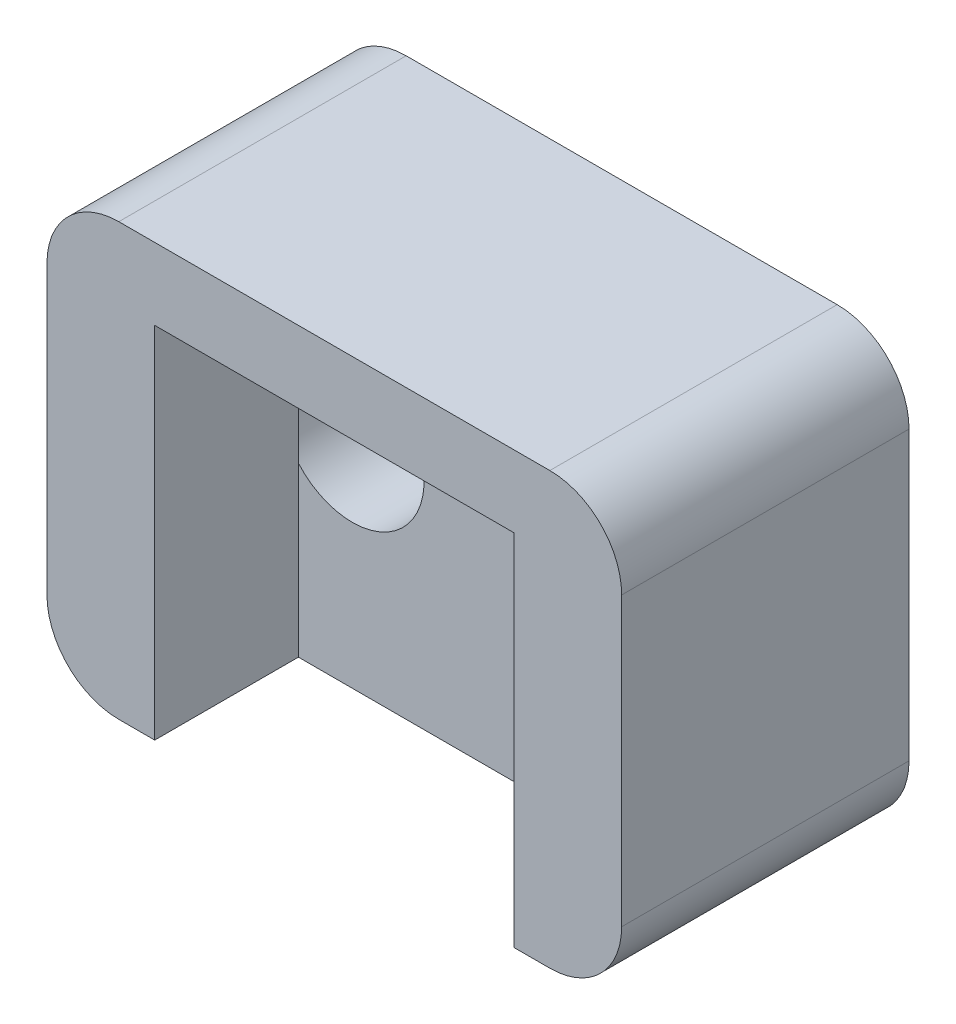
SolidWorks part; units mm, degrees
ref_plane "Front Plane" through (0, 0, 0) normal (0, 0, 1) x (1, 0, 0)
ref_plane "Top Plane" through (0, 0, 0) normal (0, 1, 0) x (1, 0, 0)
ref_plane "Right Plane" through (0, 0, 0) normal (1, 0, 0) x (0, 0, -1)
sketch "Sketch1" plane through (0, 0, 0) normal (0, 0, 1) x (1, 0, 0)
  line L0 (-20, 0) -> (20, 0) construction
  line L1 (-20, 15) -> (20, 15)
  line L2 (-20, 15) -> (-20, -15)
  line L3 (-20, -15) -> (20, -15)
  line L4 (20, 15) -> (20, -15)
  line L5 (-20, 15) -> (20, -15) construction
  line L6 (-20, -15) -> (20, 15) construction
  line L7 (-20, 15) -> (0, -15) construction
  line L8 (0, -15) -> (20, 15) construction
  point P0 (0, 0)
  dimension "D1" = 40
  dimension "D2" = 30
extrude "Boss-Extrude1" add sketch "Sketch1" along normal blind 20
fillet "Fillet1" radius 5 4 edges at (20, 15, 10) (20, -15, 10) (-20, -15, 10) (-20, 15, 10)
sketch "Sketch2" plane through (0, 0, 0) normal (0, 0, -1) x (-1, 0, 0)
  line L0 (-17.5, 7.5) -> (0, -7.5) construction
  line L1 (-17.5, 7.5) -> (17.5, 7.5)
  line L2 (-17.5, 7.5) -> (-17.5, -7.5)
  line L3 (-17.5, -7.5) -> (17.5, -7.5)
  line L4 (17.5, 7.5) -> (17.5, -7.5)
  line L5 (-17.5, 7.5) -> (17.5, -7.5) construction
  line L6 (-17.5, -7.5) -> (17.5, 7.5) construction
  line L7 (0, -7.5) -> (17.5, 7.5) construction
  circle A0 centre (-8.75, 0) radius 5
  circle A1 centre (8.75, 0) radius 5
  point P0 (0, 0)
  dimension "D3" = 10
  dimension "D1" = 35
  dimension "D2" = 15
extrude "Cut-Extrude1" cut sketch "Sketch2" against normal blind 10 contours A0 | A1
sketch "Sketch3" plane through (0, 0, 20) normal (0, 0, 1) x (1, 0, 0)
  line L0 (0, 0) -> (0, -15) construction
  line L1 (-15, -15) -> (15, -15) construction
  line L3 (-12.5, -15) -> (12.5, -15)
  line L4 (-12.5, -15) -> (-12.5, 10)
  line L5 (-12.5, 10) -> (12.5, 10)
  line L6 (12.5, -15) -> (12.5, 10)
  dimension "D1" = 12.5
  dimension "D2" = 25
  dimension "D3" = 25
extrude "Cut-Extrude2" cut sketch "Sketch3" against normal blind 10
